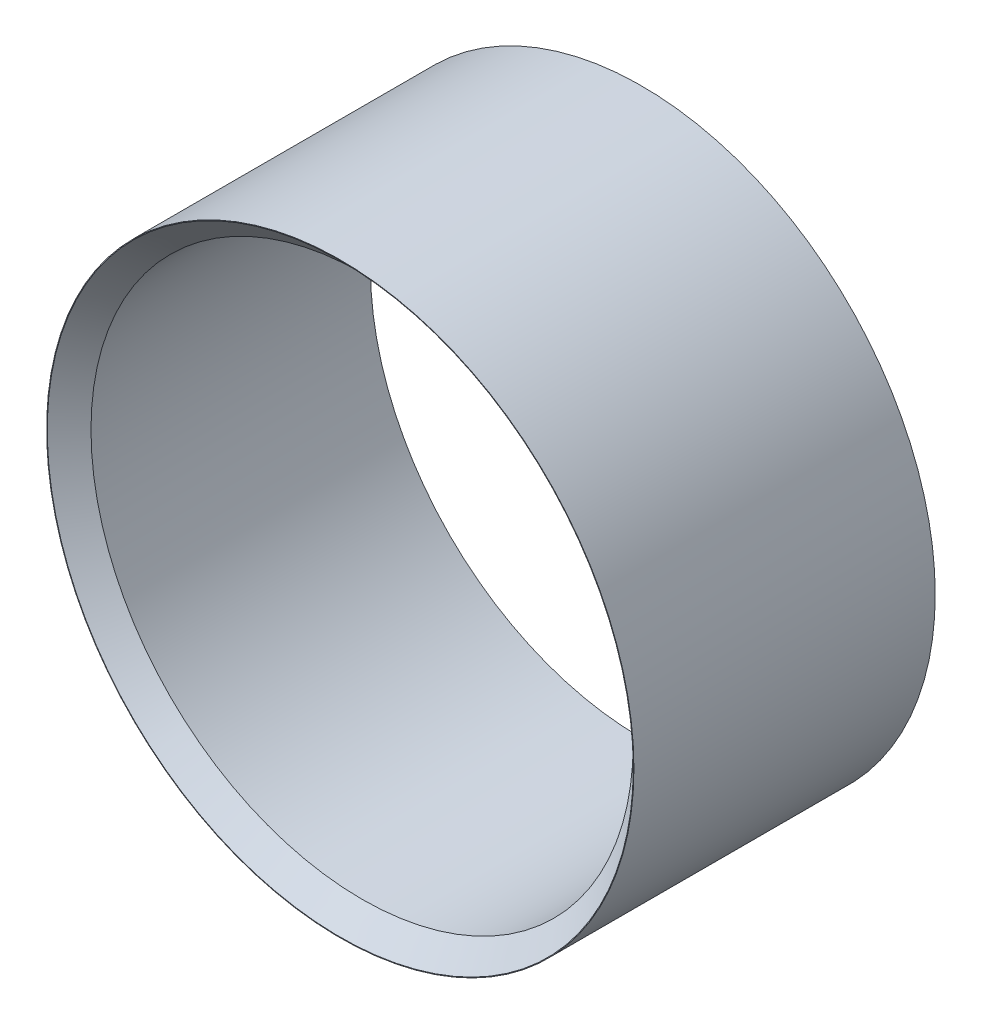
SolidWorks part; units mm, degrees
ref_plane "Front Plane" through (0, 0, 0) normal (0, 0, 1) x (1, 0, 0)
ref_plane "Top Plane" through (0, 0, 0) normal (0, 1, 0) x (1, 0, 0)
ref_plane "Right Plane" through (0, 0, 0) normal (1, 0, 0) x (0, 0, -1)
sketch "Sketch2" plane through (0, 0, 0) normal (0, 0, 1) x (1, 0, 0)
  circle A0 centre (0, 0) radius 15.748
  circle A1 centre (0, 0) radius 17.0561
  dimension "D1" = 31.496
  dimension "D2" = 34.1122
  dimension "D3" = 1.3081
extrude "Boss-Extrude1" add sketch "Sketch2" along normal blind 17.5006
chamfer "Chamfer1" distance 1.27 angle 45 1 edges at (15.748, 0, 17.5006)
